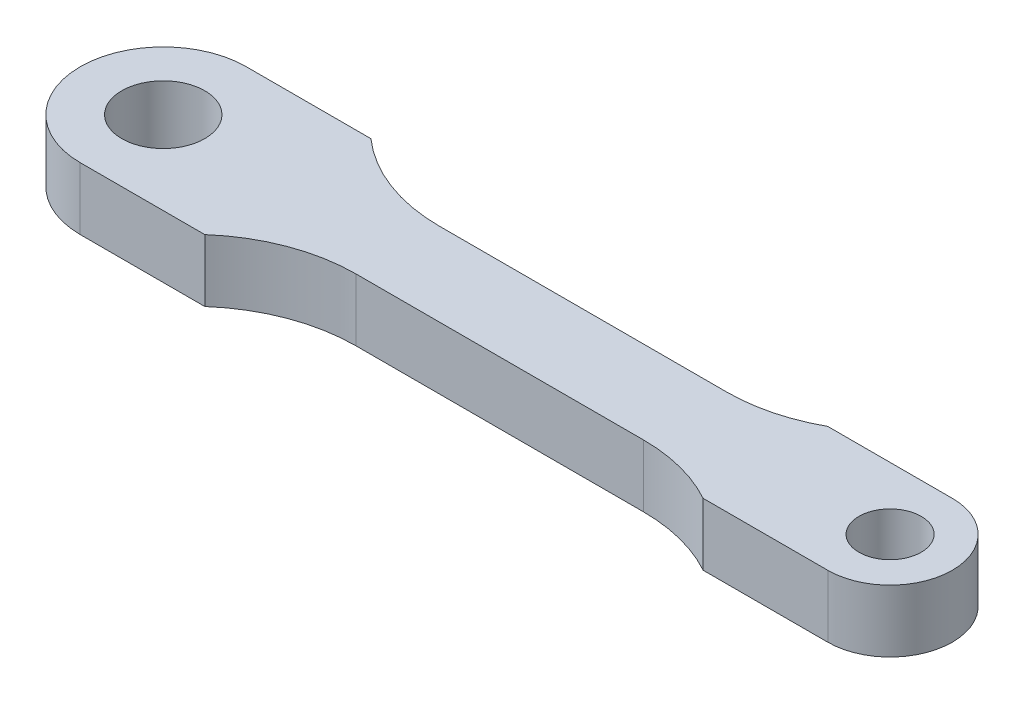
SolidWorks part; units mm, degrees
ref_plane "Front Plane" through (0, 0, 0) normal (0, 0, 1) x (1, 0, 0)
ref_plane "Top Plane" through (0, 0, 0) normal (0, 1, 0) x (1, 0, 0)
ref_plane "Right Plane" through (0, 0, 0) normal (1, 0, 0) x (0, 0, -1)
sketch "Sketch1" plane through (0, 0, 0) normal (0, 1, 0) x (1, 0, 0)
  line L0 (0, 4) -> (6, 4)
  line L1 (0, 0) -> (35, 0) construction
  line L2 (0, -4) -> (6, -4)
  line L3 (11.2915, 2) -> (25.127, 2)
  line L4 (11.2915, -2) -> (25.127, -2)
  line L5 (29, 3) -> (35, 3)
  line L6 (29, -3) -> (35, -3)
  arc A0 (0, 4) -> (0, -4) centre (0, 0) ccw
  arc A1 (6, -4) -> (11.2915, -2) centre (11.2915, -10) cw
  arc A2 (6, 4) -> (11.2915, 2) centre (11.2915, 10) ccw
  arc A3 (35, -3) -> (35, 3) centre (35, 0) ccw
  arc A4 (25.127, 2) -> (29, 3) centre (25.127, 10) ccw
  arc A5 (25.127, -2) -> (29, -3) centre (25.127, -10) cw
  circle A6 centre (0, 0) radius 2
  circle A7 centre (35, 0) radius 1.5
  point P21 (18.2093, 2)
  dimension "D1" = 8
  dimension "D2" = 6
  dimension "D3" = 8
  dimension "D4" = 8
  dimension "D9" = 4
  dimension "D10" = 3
  dimension "D5" = 4
  dimension "D6" = 35
  dimension "D7" = 6
  dimension "D8" = 6
extrude "Boss-Extrude1" add sketch "Sketch1" along normal blind 3
